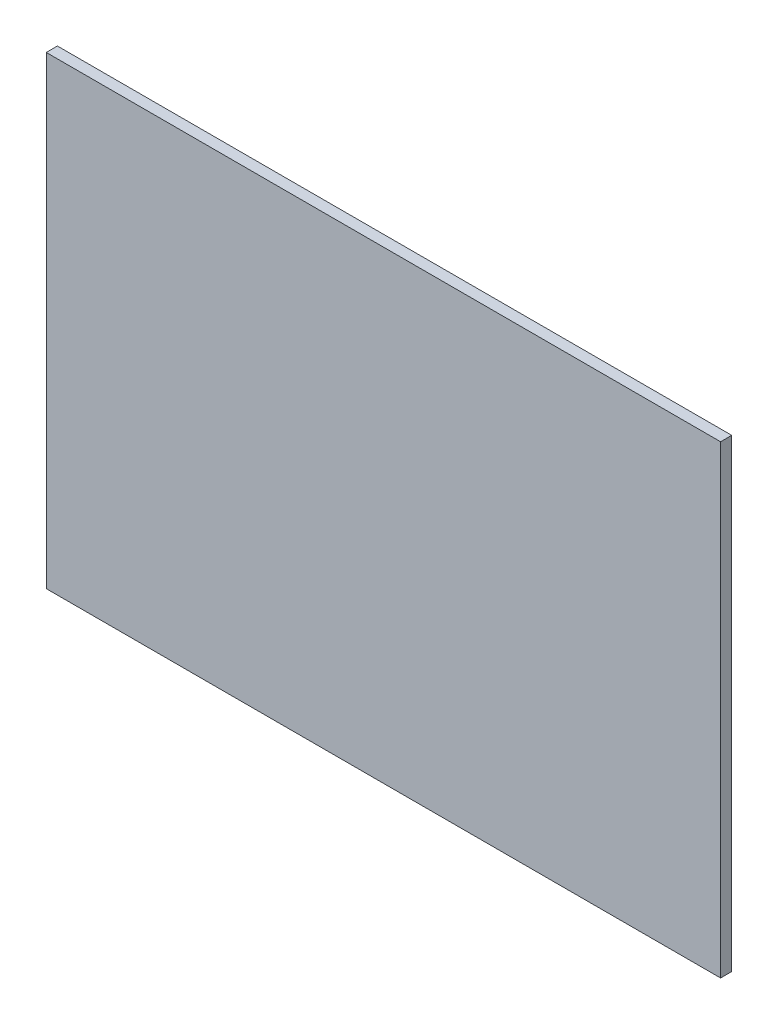
SolidWorks part; units mm, degrees
ref_plane "Front Plane" through (0, 0, 0) normal (0, 0, 1) x (1, 0, 0)
ref_plane "Top Plane" through (0, 0, 0) normal (0, 1, 0) x (1, 0, 0)
ref_plane "Right Plane" through (0, 0, 0) normal (1, 0, 0) x (0, 0, -1)
sketch "Sketch1" plane through (0, 0, 0) normal (0, 0, 1) x (1, 0, 0)
  line L1 (-363, 250) -> (363, 250)
  line L2 (-363, 250) -> (-363, -250)
  line L3 (-363, -250) -> (363, -250)
  line L4 (363, 250) -> (363, -250)
  line L5 (-363, 250) -> (363, -250) construction
  line L6 (-363, -250) -> (363, 250) construction
  point P0 (0, 0)
  dimension "D1" = 726
  dimension "D2" = 500
extrude "Boss-Extrude1" add sketch "Sketch1" along normal blind 12
equation "\"Case_Width\" = 750mm"
equation "\"Case_Height\" = 500mm"
equation "\"WoodSheet_Thickness\" = 12mm"
equation "\"D1@Boss-Extrude1\"=\"WoodSheet_Thickness\""
equation "\"D1@Sketch1\"=\"Case_Width\"-(\"WoodSheet_Thickness\"*2)"
equation "\"D2@Sketch1\"=\"Case_Height\""
